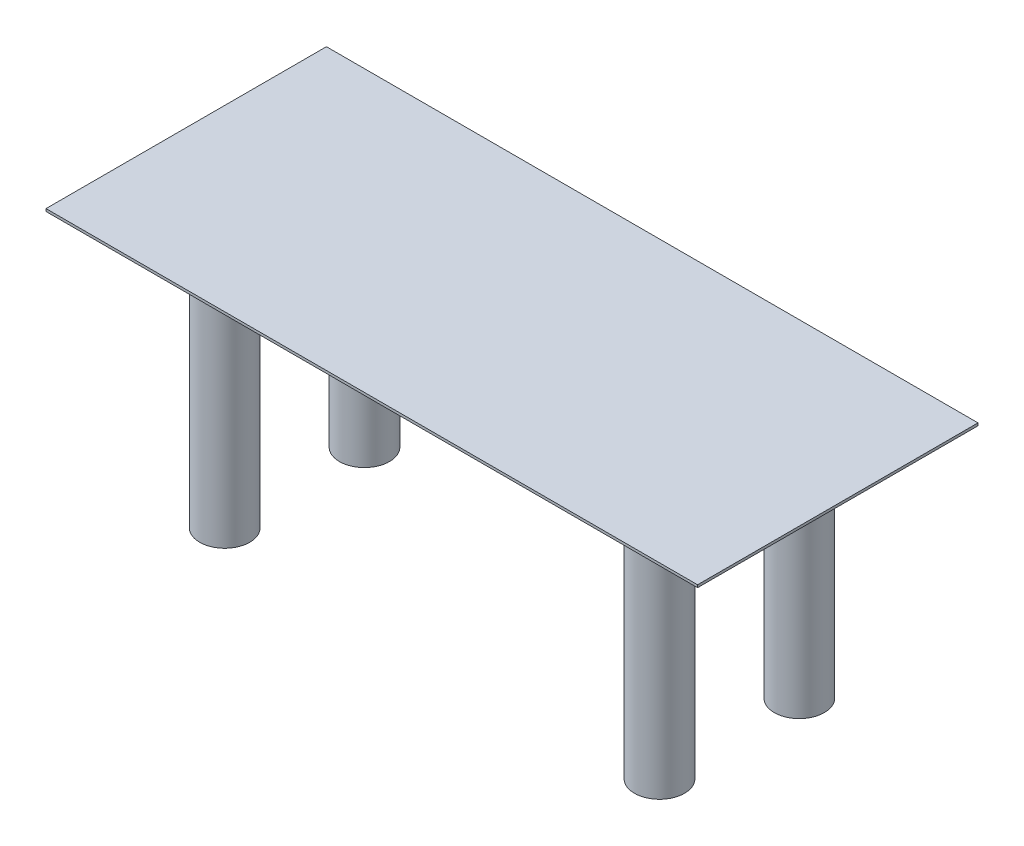
SolidWorks part; units mm, degrees
ref_plane "정면" through (0, 0, 0) normal (0, 0, 1) x (1, 0, 0)
ref_plane "윗면" through (0, 0, 0) normal (0, 1, 0) x (1, 0, 0)
ref_plane "우측면" through (0, 0, 0) normal (1, 0, 0) x (0, 0, -1)
sketch "스케치1" plane through (0, 0, 0) normal (0, 1, 0) x (1, 0, 0)
  line L1 (-1278, 550) -> (1278, 550)
  line L2 (-1278, 550) -> (-1278, -550)
  line L3 (-1278, -550) -> (1278, -550)
  line L4 (1278, 550) -> (1278, -550)
  line L5 (-1278, 550) -> (1278, -550) construction
  line L6 (-1278, -550) -> (1278, 550) construction
  point P0 (0, 0)
  dimension "D1" = 2556
  dimension "D2" = 1100
extrude "보스-돌출1" add sketch "스케치1" along normal blind 10
sketch "스케치2" plane through (0, 0, 0) normal (0, -1, 0) x (-1, 0, 0)
  line L0 (1278, 0) -> (-1278, 0) construction
  line L1 (1278, 550) -> (1278, -550) construction
  line L2 (-1278, -550) -> (-1278, 550) construction
  line L3 (0, -550) -> (0, 550) construction
  line L4 (1278, -550) -> (-1278, -550) construction
  line L5 (-1278, 550) -> (1278, 550) construction
  circle A0 centre (852.8503, -274.1841) radius 98.1775
  circle A1 centre (-852.8503, -274.1841) radius 98.1775
  circle A2 centre (-852.8503, 274.1841) radius 98.1775
  circle A3 centre (852.8503, 274.1841) radius 98.1775
extrude "보스-돌출2" add sketch "스케치2" along normal blind 1000
